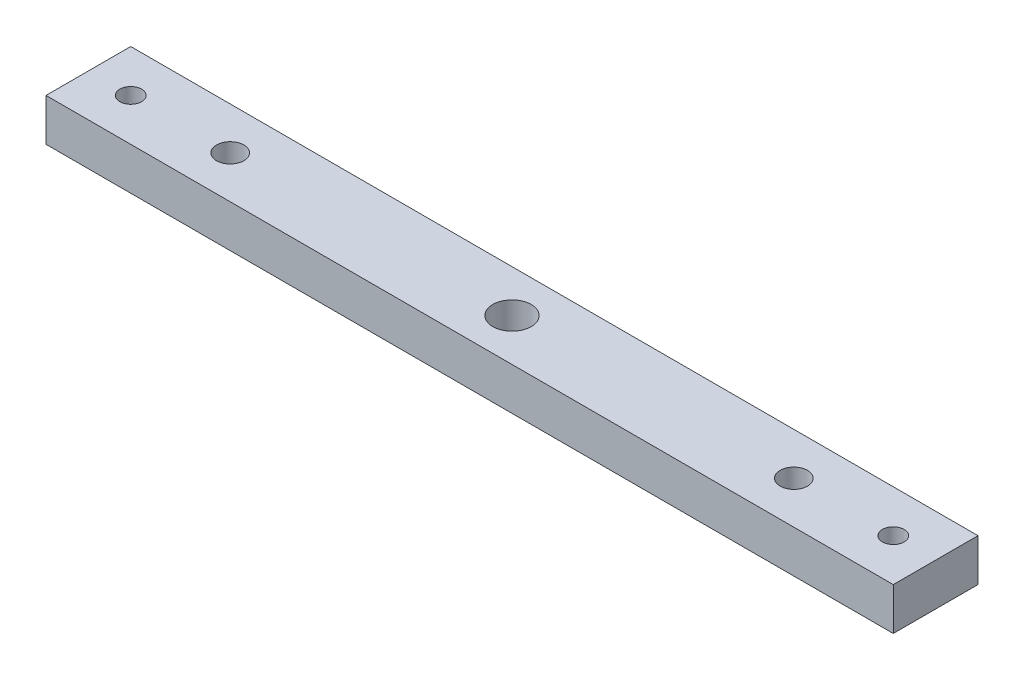
SolidWorks part; units mm, degrees
material "6061 Alloy"
ref_plane "Front Plane" through (0, 0, 0) normal (0, 0, 1) x (1, 0, 0)
ref_plane "Top Plane" through (0, 0, 0) normal (0, 1, 0) x (1, 0, 0)
ref_plane "Right Plane" through (0, 0, 0) normal (1, 0, 0) x (0, 0, -1)
sketch "Sketch1" plane through (0, 0, 0) normal (0, 1, 0) x (1, 0, 0)
  line L1 (0, 0) -> (-254, 0)
  line L2 (0, 0) -> (0, 25.4)
  line L3 (0, 25.4) -> (-254, 25.4)
  line L4 (-254, 0) -> (-254, 25.4)
  dimension "D2" = 25.4
  dimension "D1" = 254
extrude "Boss-Extrude1" add sketch "Sketch1" along normal blind 12.7
sketch "Sketch2" plane through (0, 12.7, 0) normal (0, 1, 0) x (1, 0, 0)
  line L0 (-127, 12.7) -> (-127, 25.4) construction
  line L1 (0, 25.4) -> (-254, 25.4) construction
  line L2 (-127, 12.7) -> (-127, 0) construction
  line L3 (-254, 0) -> (0, 0) construction
  circle A0 centre (-127, 12.7) radius 5.08
  dimension "D1" = 10.16
extrude "1/2-20 thread thru" cut sketch "Sketch2" against normal through all
sketch "Sketch3" plane through (0, 0, 0) normal (0, -1, 0) x (1, 0, 0)
  line L0 (-254, -12.7) -> (-215.9635, -12.7) construction
  line L1 (-254, -25.4) -> (-254, 0) construction
  line L2 (-254, -12.7) -> (-198.0565, -12.7) construction
  line L3 (0, -12.7) -> (-38.0365, -12.7) construction
  line L4 (0, 0) -> (0, -25.4) construction
  line L5 (0, -12.7) -> (-55.9435, -12.7) construction
  circle A0 centre (-38.0365, -12.7) radius 2.0193
  circle A1 centre (-55.9435, -12.7) radius 2.0193
  circle A2 centre (-215.9635, -12.7) radius 2.0193
  circle A3 centre (-198.0565, -12.7) radius 2.0193
  dimension "D3" = 4.0386
  dimension "D1" = 38.0365
  dimension "D2" = 55.9435
extrude "Cut-Extrude3" [suppressed] cut sketch "Sketch3" against normal blind 10.16
sketch "Sketch4" plane through (0, 0, 0) normal (0, -1, 0) x (1, 0, 0)
  line L0 (-127, -12.7) -> (-211.4804, -12.7) construction
  line L1 (-127, -12.7) -> (-42.5196, -12.7) construction
  circle A0 centre (-211.4804, -12.7) radius 4.1021
  circle A1 centre (-42.5196, -12.7) radius 4.1021
  dimension "D2" = 8.2042
  dimension "D1" = 84.4804
extrude "Cut-Extrude4" cut sketch "Sketch4" against normal through all
sketch "Sketch5" plane through (0, 0, 0) normal (0, -1, 0) x (-1, 0, 0)
  line L0 (241.3, 12.7) -> (254, 12.7) construction
  line L1 (254, 25.4) -> (254, 0) construction
  line L2 (241.3, 12.7) -> (241.3, 25.4) construction
  line L3 (0, 25.4) -> (254, 25.4) construction
  line L4 (12.7, 12.7) -> (0, 12.7) construction
  line L5 (0, 0) -> (0, 25.4) construction
  line L6 (12.7, 12.7) -> (12.7, 25.4) construction
hole_wizard "CSK for 1/4 Flat Head Machine Screw1" positions "Sketch6" profile "Sketch7" countersink size "1/4" standard "ANSI Inch"
sketch "Sketch6" plane through (0, 0, 0) normal (0, -1, 0) x (-1, 0, 0)
  point P0 (241.3, 12.7)
  point P3 (12.7, 12.7)
sketch "Sketch7" plane through (-241.3, 0, -12.7) normal (1, 0, 0) x (0, 0, -1)
  line L0 (0, 0) -> (0, 12.7)
  line L1 (0, 12.7) -> (3.2639, 12.7)
  line L2 (3.2639, 12.7) -> (3.2639, 3.6524)
  line L3 (3.2639, 3.6524) -> (6.4389, 0)
  line L5 (6.4389, 0) -> (0, 0)
  line L6 (-3.2639, 3.6524) -> (-6.4389, 0) construction
  line L11 (0, -6.35) -> (0, 107.95) construction
  dimension "Thru Hole Dia." = 6.5278
  dimension "Thru Hole Depth" = 12.7
  dimension "Near C'Sink Dia." = 12.8778
  dimension "Near C'Sink Angle" = 82
hole_wizard "1/2-20 Tapped Hole3" positions "Sketch14" profile "Sketch15" tap size "1/2-20" standard "ANSI Inch" end condition through all
sketch "Sketch14" plane through (0, 12.7, 0) normal (0, 1, 0) x (1, 0, 0)
  point P0 (-127, 12.7)
sketch "Sketch15" plane through (-127, 12.7, -12.7) normal (1, 0, 0) x (0, 0, 1)
  line L0 (0, 0) -> (0, 12.7)
  line L1 (0, 12.7) -> (5.7544, 12.7)
  line L2 (5.7544, 12.7) -> (5.7544, 0)
  line L5 (5.7544, 0) -> (0, 0)
  line L11 (0, -6.35) -> (0, 107.95) construction
  dimension "Thru Tap Drill Dia." = 11.5087
  dimension "Thru Tap Drill Depth" = 12.7
cosmetic thread "Hole Thread1"
sketch3d "Sketch_MAC1-1_TOPBEAM_MILLING" [suppressed]
  line L0 (-254, 0, -25.4) -> (-244, 0, -25.4)
  line L1 (-254, 0, -25.4) -> (-254, 0, -15.4)
  point P0 (-254, 0, -25.4)
  point P1 (-244, 0, -25.4)
  point P2 (-254, 0, -15.4)
sketch3d "Stock_TOPBEAM_MILLING"
  line L0 (-254, 12.7, -25.4) -> (0, 12.7, -25.4)
  line L1 (0, 12.7, -25.4) -> (0, 12.7, 0)
  line L2 (0, 12.7, 0) -> (-254, 12.7, 0)
  line L3 (-254, 12.7, 0) -> (-254, 12.7, -25.4)
  line L4 (-254, 0, -25.4) -> (0, 0, -25.4)
  line L5 (0, 0, -25.4) -> (0, 0, 0)
  line L6 (0, 0, 0) -> (-254, 0, 0)
  line L7 (-254, 0, 0) -> (-254, 0, -25.4)
  line L8 (-254, 12.7, -25.4) -> (-254, 0, -25.4)
  line L9 (0, 12.7, -25.4) -> (0, 0, -25.4)
  line L10 (0, 12.7, 0) -> (0, 0, 0)
  line L11 (-254, 12.7, 0) -> (-254, 0, 0)
  point P8 (-127, 12.7, -25.4)
  point P9 (0, 12.7, -12.7)
  point P10 (-127, 12.7, 0)
  point P11 (-254, 12.7, -12.7)
  point P12 (-127, 0, -25.4)
  point P13 (0, 0, -12.7)
  point P14 (-127, 0, 0)
  point P15 (-254, 0, -12.7)
  point P16 (-254, 6.35, -25.4)
  point P17 (0, 6.35, -25.4)
  point P18 (0, 6.35, 0)
  point P19 (-254, 6.35, 0)
  point P20 (-127, 6.35, -12.7)
  point P21 (-127, 6.35, -25.4)
  point P22 (-127, 0, -12.7)
  point P23 (-127, 6.35, 0)
  point P24 (-127, 12.7, -12.7)
  point P25 (-254, 6.35, -12.7)
  point P26 (0, 6.35, -12.7)
equation "\"cross_length\"=10"
equation "\"wing_spar_height\"= 2"
equation "\"wing_spar_thickness\"= .5"
equation "\"frame_width\"= 10"
equation "\"D1@Sketch1\"=\"frame_width\""
